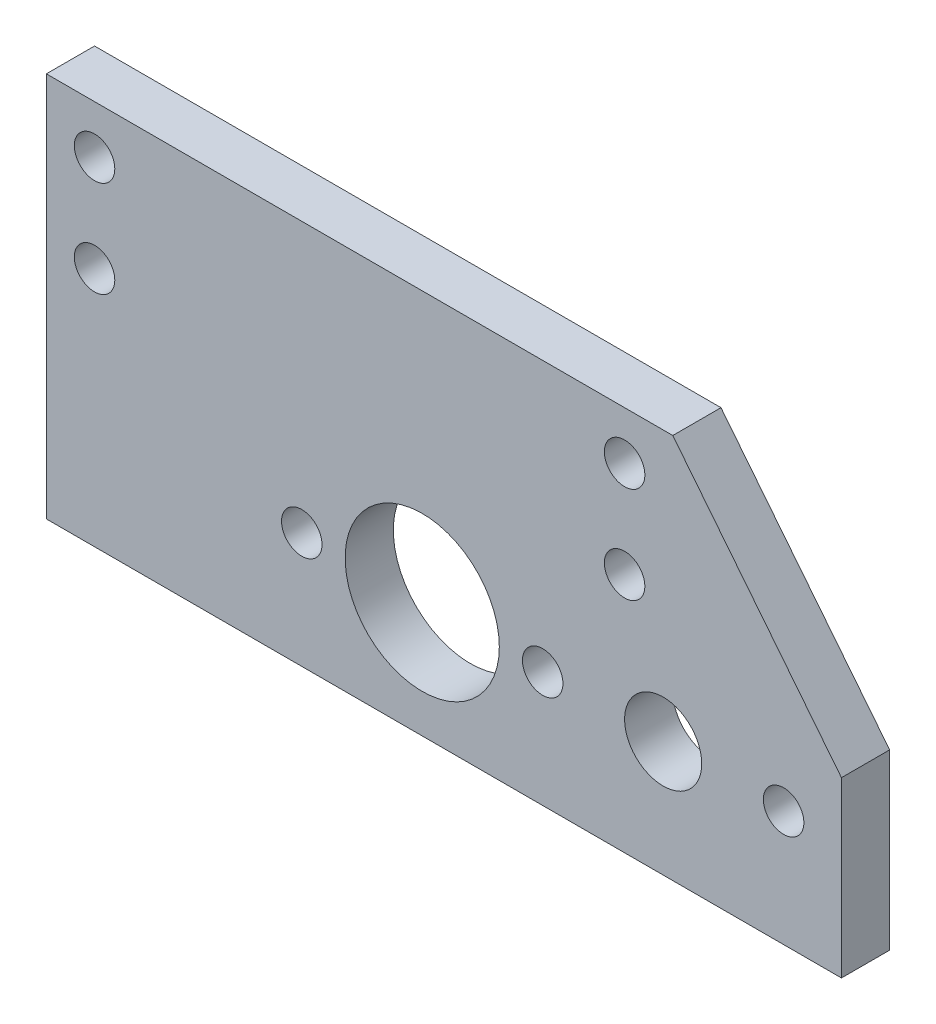
SolidWorks part; units mm, degrees
ref_plane "Front Plane" through (0, 0, 0) normal (0, 0, 1) x (1, 0, 0)
ref_plane "Top Plane" through (0, 0, 0) normal (0, 1, 0) x (1, 0, 0)
ref_plane "Right Plane" through (0, 0, 0) normal (1, 0, 0) x (0, 0, -1)
sketch "Sketch1" plane through (0, 0, 0) normal (0, 0, 1) x (1, 0, 0)
  line L3 (116.6115, 15.3385) -> (51.6115, 15.3385)
  line L4 (51.6115, 15.3385) -> (51.6115, -6.6615)
  line L8 (51.6115, -24.6615) -> (116.6115, -24.6615)
  line L9 (51.6115, -6.6615) -> (51.6115, -24.6615)
  line L10 (134.1115, -6.6615) -> (134.1115, -24.6615)
  line L11 (134.1115, -24.6615) -> (116.6115, -24.6615)
  line L12 (116.6115, 15.3385) -> (134.1115, -6.6615)
  circle A0 centre (56.6115, 10.3385) radius 2.1
  circle A1 centre (111.6115, 10.3385) radius 2.1
  circle A2 centre (56.6115, 0.3385) radius 2.1
  circle A3 centre (111.6115, 0.3385) radius 2.1
  circle A8 centre (115.6115, -12.6615) radius 4
  circle A9 centre (90.6115, -12.6615) radius 8
  circle A10 centre (78.1115, -12.6615) radius 2.1
  circle A11 centre (103.1115, -12.6615) radius 2.1
  circle A12 centre (128.1115, -12.6615) radius 2.1
  dimension "D7" = 4.2
  dimension "D8" = 4.2
  dimension "D9" = 4.2
  dimension "D10" = 4.2
  dimension "D11" = 5
  dimension "D12" = 5
  dimension "D13" = 17.5
  dimension "D14" = 5
  dimension "D15" = 1
  dimension "D16" = 10
  dimension "D17" = 10
  dimension "D18" = 5
  dimension "D19" = 8
  dimension "D20" = 16
  dimension "D21" = 25
  dimension "D23" = 4.2
  dimension "D24" = 12.5
  dimension "D25" = 4.2
  dimension "D26" = 12.5
  dimension "D27" = 4.2
  dimension "D28" = 12.5
  dimension "D2" = 65
  dimension "D4" = 40
  dimension "D5" = 22
extrude "Boss-Extrude1" add sketch "Sketch1" along normal blind 5
sketch "Sketch2" plane through (0, 0, 5) normal (0, 0, 1) x (1, 0, 0)
  line L0 (90.6115, -12.6615) -> (90.6115, 19.4472) construction
  line L1 (116.6115, 15.3385) -> (51.6115, 15.3385) construction
  circle A1 centre (90.6115, 15.3385) radius 15
  point P0 (90.6115, 15.3385)
move or copy body "Body-Move/Copy1" [suppressed] bodies to move or copy 101
